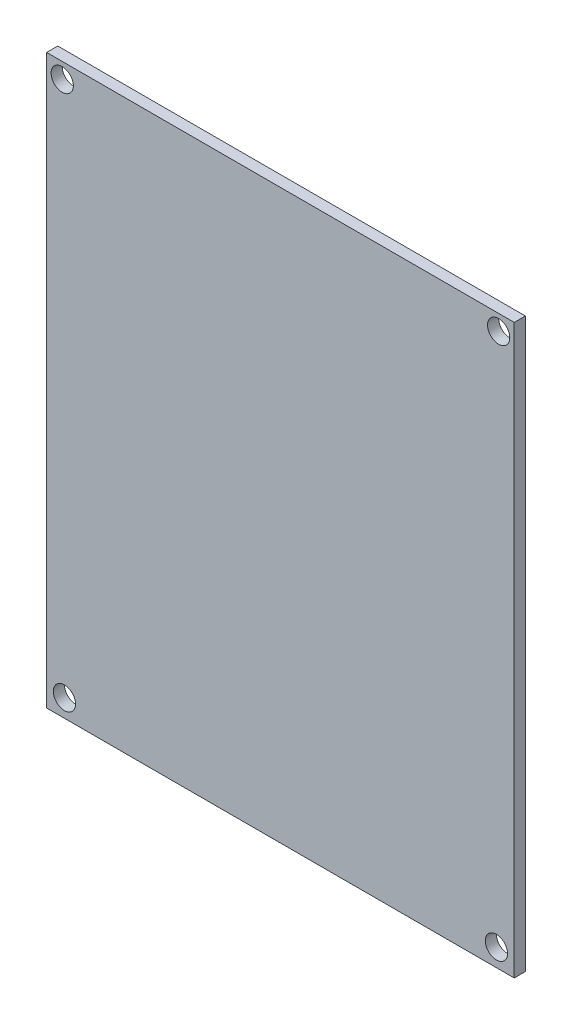
SolidWorks part; units mm, degrees
ref_plane "Alzado" through (0, 0, 0) normal (0, 0, 1) x (1, 0, 0)
ref_plane "Planta" through (0, 0, 0) normal (0, 1, 0) x (1, 0, 0)
ref_plane "Vista lateral" through (0, 0, 0) normal (1, 0, 0) x (0, 0, -1)
sketch "Croquis1" plane through (0, 0, 0) normal (0, 0, 1) x (1, 0, 0)
  line L1 (105, -317.2155) -> (-105, -317.2155)
  line L2 (105, -317.2155) -> (105, -62.2155)
  line L3 (105, -62.2155) -> (-105, -62.2155)
  line L4 (-105, -317.2155) -> (-105, -62.2155)
  circle A0 centre (-97, -309.2155) radius 5
  circle A1 centre (97, -309.2155) radius 5
  circle A2 centre (98, -69.2155) radius 5
  circle A3 centre (-98, -69.2155) radius 5
extrude "Saliente-Extruir1" add sketch "Croquis1" along normal blind 5
